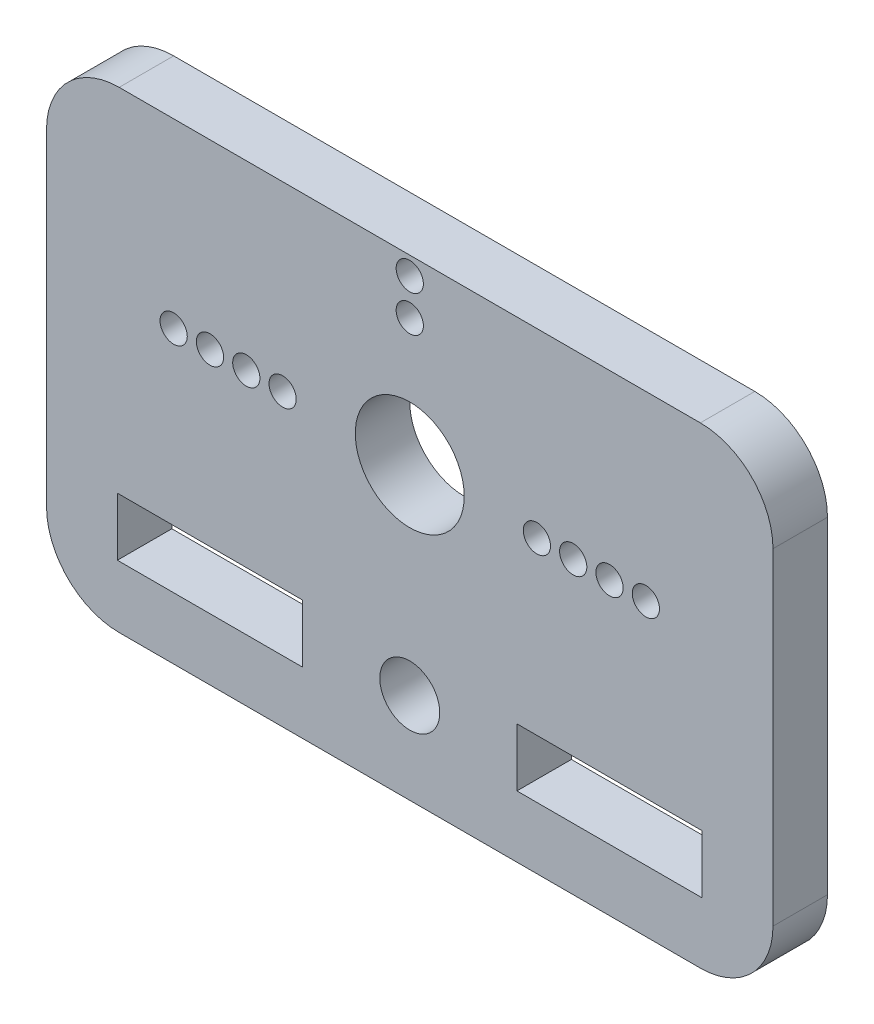
SolidWorks part; units mm, degrees
ref_plane "Спереди" through (0, 0, 0) normal (0, 0, 1) x (1, 0, 0)
ref_plane "Сверху" through (0, 0, 0) normal (0, 1, 0) x (1, 0, 0)
ref_plane "Справа" through (0, 0, 0) normal (1, 0, 0) x (0, 0, -1)
other "Configuration Table"
sketch "Eskiz_kontur" plane through (0, 0, 0) normal (0, 0, 1) x (1, 0, 0)
  line L0 (-20, -12) -> (-20, 6)
  line L1 (16, -16) -> (-16, -16)
  line L2 (-16, 10) -> (16, 10)
  line L3 (20, 6) -> (20, -12)
  line L4 (-5.9, -12.6) -> (-5.9, -9.4)
  line L5 (-5.9, -9.4) -> (-16.1, -9.4)
  line L6 (-16.1, -12.6) -> (-5.9, -12.6)
  line L7 (-16.1, -9.4) -> (-16.1, -12.6)
  line L8 (16.1, -12.6) -> (16.1, -9.4)
  line L9 (16.1, -9.4) -> (5.9, -9.4)
  line L10 (5.9, -12.6) -> (16.1, -12.6)
  line L11 (5.9, -9.4) -> (5.9, -12.6)
  arc A0 (-16, -16) -> (-20, -12) centre (-16, -12) cw
  arc A1 (-20, 6) -> (-16, 10) centre (-16, 6) cw
  arc A2 (20, -12) -> (16, -16) centre (16, -12) cw
  arc A3 (16, 10) -> (20, 6) centre (16, 6) cw
extrude "Plastina" add sketch "Eskiz_kontur" along normal blind 3
sketch "Eskiz_otverstiya" plane through (0, 0, 0) normal (0, 0, 1) x (1, 0, 0)
  circle A0 centre (0, -11) radius 1.65
  circle A1 centre (-13, 0) radius 0.75
  circle A2 centre (-11, 0) radius 0.75
  circle A3 centre (-9, 0) radius 0.75
  circle A4 centre (-7, 0) radius 0.75
  circle A5 centre (0, 0) radius 3
  circle A6 centre (7, 0) radius 0.75
  circle A7 centre (9, 0) radius 0.75
  circle A8 centre (11, 0) radius 0.75
  circle A9 centre (13, 0) radius 0.75
  circle A10 centre (0, 7) radius 0.75
  circle A11 centre (0, 9) radius 0.75
  dimension "d1" = 3.3
  dimension "d2" = 1.5
  dimension "d3" = 1.5
  dimension "d4" = 1.5
  dimension "d5" = 1.5
  dimension "d6" = 6
  dimension "d7" = 1.5
  dimension "d8" = 1.5
  dimension "d9" = 1.5
  dimension "d10" = 1.5
  dimension "d11" = 1.5
  dimension "d12" = 1.5
extrude "Otverstiya" cut sketch "Eskiz_otverstiya" against normal through all and the other way through all
equation "\"T3\" = 3"
equation "\"T5\" = 5"
equation "\"D_M3\" = 3.3"
equation "\"D_M2\" = 2.2"
equation "\"D_M3_TAP\" = 2.5"
equation "\"D_M4\" = 4.5"
equation "\"L1\" = 100"
equation "\"L2\" = 100"
equation "\"D1@Plastina\" = \"T3\""
equation "\"d1@Eskiz_otverstiya\" = \"D_M3\""
